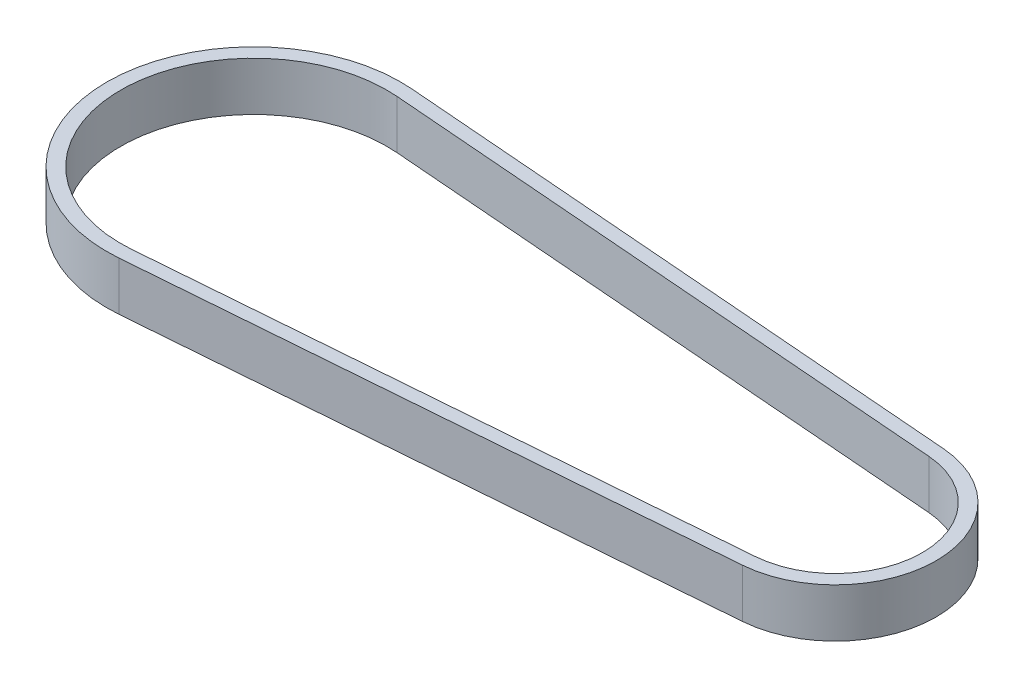
SolidWorks part; units mm, degrees
ref_plane "前视基准面" through (0, 0, 0) normal (0, 0, 1) x (1, 0, 0)
ref_plane "上视基准面" through (0, 0, 0) normal (0, 1, 0) x (1, 0, 0)
ref_plane "右视基准面" through (0, 0, 0) normal (1, 0, 0) x (0, 0, -1)
sketch "草图1" plane through (0, 0, 0) normal (0, 1, 0) x (1, 0, 0)
  line L5 (0, 0) -> (83.48, 0)
  line L6 (1.6665, 21.0291) -> (84.6255, 14.4547)
  line L7 (1.5085, 19.0353) -> (84.4675, 12.4609)
  line L8 (84.6255, -14.4547) -> (1.6665, -21.0291)
  line L10 (84.4675, -12.4609) -> (1.5085, -19.0353)
  arc A6 (1.5085, 19.0353) -> (1.5085, -19.0353) centre (0, 0) ccw
  arc A7 (84.4675, -12.4609) -> (84.4675, 12.4609) centre (83.48, 0) ccw
  arc A8 (84.6255, -14.4547) -> (84.6255, 14.4547) centre (83.48, 0) ccw
  arc A9 (1.6665, 21.0291) -> (1.6665, -21.0291) centre (0, 0) ccw
  dimension "D1" = 83.48
  dimension "D2" = 25
  dimension "D3" = 38.19
  dimension "D4" = 2
extrude "凸台-拉伸1" add sketch "草图1" along normal blind 7 contours L6 A9 L8 A8 A7 L10 A6 L7
